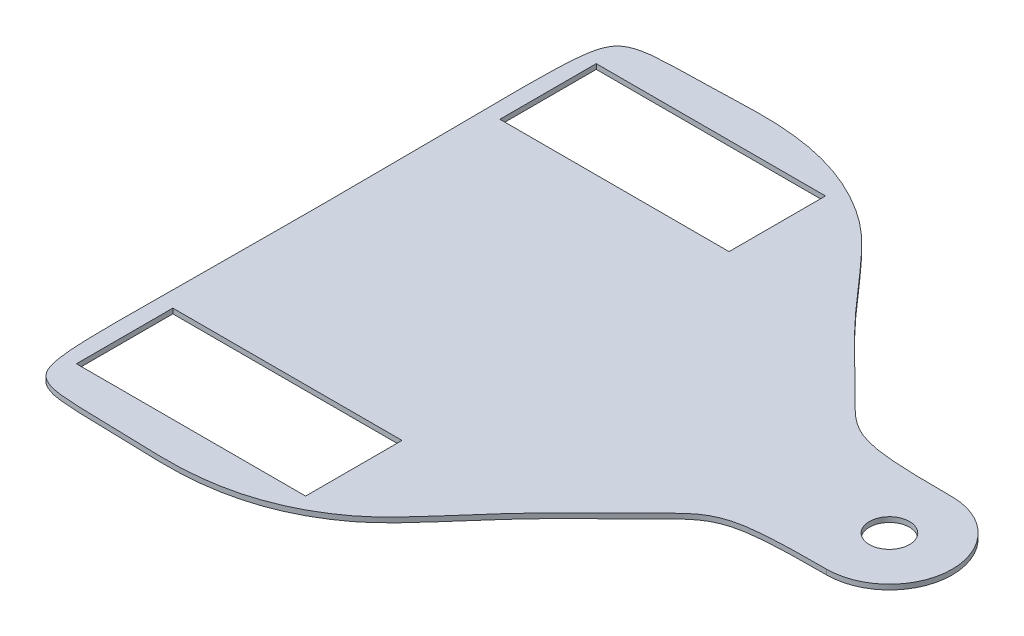
SolidWorks part; units mm, degrees
material "PLA"
ref_plane "Front Plane" through (0, 0, 0) normal (0, 0, 1) x (1, 0, 0)
ref_plane "Top Plane" through (0, 0, 0) normal (0, 1, 0) x (1, 0, 0)
ref_plane "Right Plane" through (0, 0, 0) normal (1, 0, 0) x (0, 0, -1)
sketch "base dimensions" plane through (0, 0, 0) normal (0, 1, 0) x (1, 0, 0)
  line L0 (0, 0) -> (-116.6267, 0) construction
  line L2 (-112.85, 41.1) -> (-112.85, -41.1)
  line L3 (-96.85, 41.1) -> (-96.85, -41.1)
  line L5 (-112.85, 41.1) -> (-96.85, -41.1) construction
  line L6 (-96.85, 41.1) -> (-112.85, -41.1) construction
  line L7 (-131.85, -27.5) -> (-114.85, -27.5)
  line L8 (-131.85, -27.5) -> (-131.85, 27.5)
  line L9 (-114.85, -27.5) -> (-114.85, 27.5)
  line L10 (-131.85, 27.5) -> (-114.85, 27.5)
  line L11 (-131.85, -27.5) -> (-114.85, 27.5) construction
  line L12 (-114.85, -27.5) -> (-131.85, 27.5) construction
  line L13 (-94.85, 0) -> (-94.85, 10.9056)
  line L14 (-135.85, -577.028) -> (-135.85, 577.028) construction
  line L16 (-130.25, -60.15) -> (-79.45, -60.15)
  line L17 (-130.25, 41.1) -> (-79.45, 41.1)
  line L18 (-130.25, 41.1) -> (-130.25, 60.15)
  line L19 (-130.25, 60.15) -> (-79.45, 60.15)
  line L20 (-79.45, 41.1) -> (-79.45, 60.15)
  line L21 (-79.45, -41.1) -> (-79.45, -60.15)
  line L22 (-130.25, -41.1) -> (-79.45, -41.1)
  line L23 (-130.25, -41.1) -> (-130.25, -60.15)
  circle A0 centre (0, 0) radius 63.5 construction
  circle A1 centre (0, 0) radius 15
  circle A2 centre (-81, 0) radius 13.85
  spline S0 degree 3 poles (0, 15) (-26.0597, 15) (-24.2984, 16.8762) (-51.0086, 41.9815) (-61.2896, 55.9447) (-79.9531, 69.6921) (-95.0158, 71.7163) (-110.819, 71.0052) (-126.522, 70.8741) (-138.1428, 68.2179) (-135.85, 61.1511) (-135.85, 0) knots 0 0 0 0 0.141138 0.170317 0.278296 0.317035 0.518967 0.554463 0.636493 0.682072 1 1 1 1
  spline S1 degree 3 poles (0, -15) (-26.0597, -15) (-24.2984, -16.8762) (-51.0086, -41.9815) (-61.2896, -55.9447) (-79.9531, -69.6921) (-95.0158, -71.7163) (-110.819, -71.0052) (-126.522, -70.8741) (-138.1428, -68.2179) (-135.85, -61.1511) (-135.85, 0) knots 0 0 0 0 0.141138 0.170317 0.278296 0.317035 0.518967 0.554463 0.636493 0.682072 1 1 1 1
  point P4 (-96.85, 0)
  point P8 (-67.15, 0)
  point P10 (-104.85, 0)
  point P11 (-63.5, 0)
  point P20 (-123.35, 0)
  point P27 (-114.85, 0)
  dimension "D1" = 127
  dimension "D2" = 30
  dimension "D5" = 27.7
  dimension "D9" = 2
  dimension "D10" = 81
  dimension "D15" = 90
  dimension "D3" = 82.2
  dimension "D4" = 16
  dimension "D6" = 55
  dimension "D7" = 17
  dimension "D8" = 2
  dimension "D11" = 19.05
  dimension "D12" = 50.8
  dimension "D14" = 3.65
  dimension "D18" = 4
extrude "Boss-Extrude1" add sketch "base dimensions" against normal blind 1.2
sketch "Sketch2" plane through (0, -1.2, 0) normal (0, -1, 0) x (-1, 0, 0)
  line L4 (-200000, 0) -> (200116.6267, 0) construction
  line L5 (-200000, 0) -> (200116.6267, 0)
  line L8 (132.25, 39.1) -> (132.25, 62.15)
  line L9 (77.45, 39.1) -> (132.25, 39.1)
  line L10 (77.45, 62.15) -> (77.45, 39.1)
  line L11 (132.25, 62.15) -> (77.45, 62.15)
  line L12 (132.25, 39.1) -> (132.25, 62.15)
  line L13 (77.45, 39.1) -> (132.25, 39.1)
  line L14 (77.45, 62.15) -> (77.45, 39.1)
  line L15 (132.25, 62.15) -> (77.45, 62.15)
  line L22 (77.45, -62.15) -> (132.25, -62.15)
  line L23 (77.45, -39.1) -> (77.45, -62.15)
  line L24 (132.25, -39.1) -> (77.45, -39.1)
  line L25 (132.25, -62.15) -> (132.25, -39.1)
  line L26 (77.45, -62.15) -> (132.25, -62.15)
  line L27 (77.45, -39.1) -> (77.45, -62.15)
  line L28 (132.25, -39.1) -> (77.45, -39.1)
  line L29 (132.25, -62.15) -> (132.25, -39.1)
  dimension "D1" = 2
  dimension "D2" = 2
extrude "Cut-Extrude1" cut sketch "Sketch2" against normal through all
sketch "Sketch4" plane through (0, 0, 0) normal (0, 1, 0) x (1, 0, 0)
  circle A3 centre (0, 0) radius 4.7879
  dimension "D1" = 9.5758
extrude "Cut-Extrude2" cut sketch "Sketch4" against normal through all
